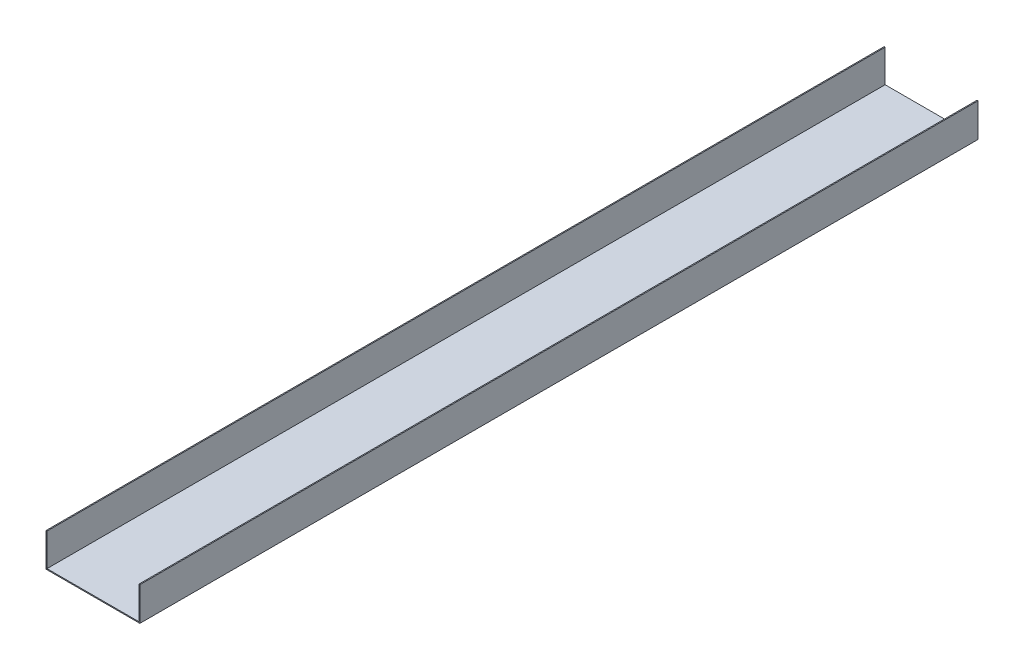
SolidWorks part; units mm, degrees
ref_plane "Спереди" through (0, 0, 0) normal (0, 0, 1) x (1, 0, 0)
ref_plane "Сверху" through (0, 0, 0) normal (0, 1, 0) x (1, 0, 0)
ref_plane "Справа" through (0, 0, 0) normal (1, 0, 0) x (0, 0, -1)
sketch "Эскиз1" plane through (0, 0, 0) normal (0, 0, 1) x (1, 0, 0)
  line L0 (-70, -1.5) -> (70, -1.5)
  line L1 (70, -1.5) -> (70, 48.5)
  line L2 (70, 48.5) -> (68.5, 48.5)
  line L3 (68.5, 48.5) -> (68.5, 0)
  line L4 (68.5, 0) -> (-68.5, 0)
  line L5 (-68.5, 0) -> (-68.5, 48.5)
  line L6 (-68.5, 48.5) -> (-70, 48.5)
  line L7 (-70, 48.5) -> (-70, -1.5)
  point P3 (119.2997, 74.5762)
  dimension "D1" = 140
  dimension "D2" = 50
  dimension "D3" = 1.5
  dimension "D4" = 48.5
extrude "Бобышка-Вытянуть2" add sketch "Эскиз1" along normal blind 1250
